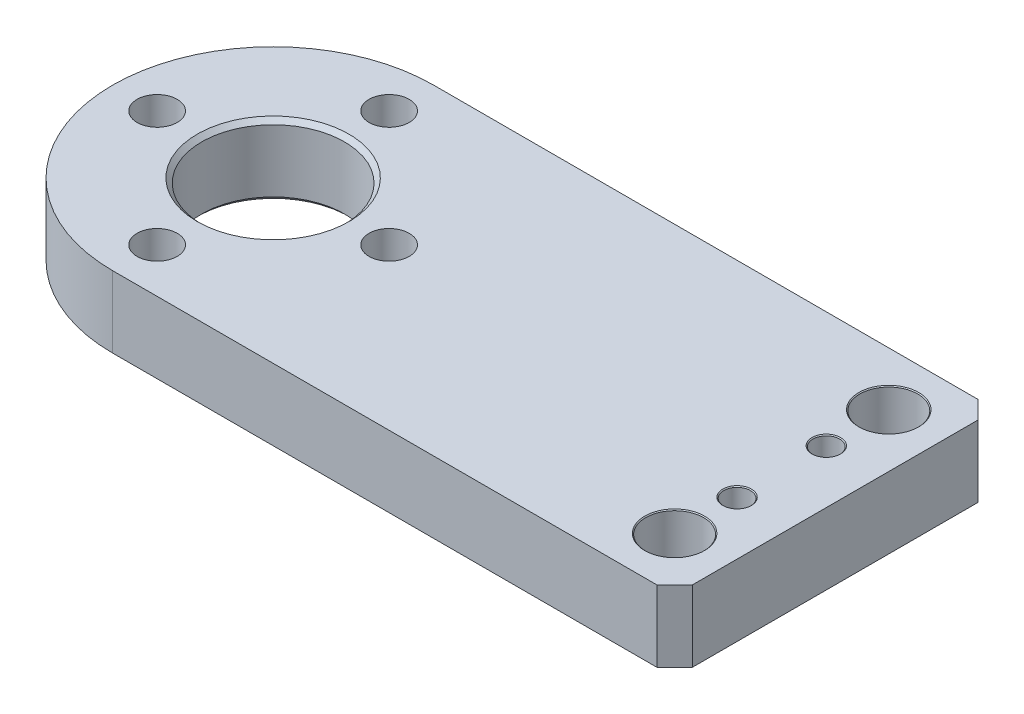
SolidWorks part; units mm, degrees
ref_plane "Front Plane" through (0, 0, 0) normal (0, 0, 1) x (1, 0, 0)
ref_plane "Top Plane" through (0, 0, 0) normal (0, 1, 0) x (1, 0, 0)
ref_plane "Right Plane" through (0, 0, 0) normal (1, 0, 0) x (0, 0, -1)
sketch "Sketch1" plane through (0, 0, 0) normal (0, 1, 0) x (1, 0, 0)
  line L0 (0, 0) -> (67.6829, 0) construction
  line L1 (0, 18) -> (61, 18)
  line L2 (63, 16) -> (63, -16)
  line L3 (0, -18) -> (61, -18)
  line L4 (61, 18) -> (63, 16)
  line L5 (61, -18) -> (63, -16)
  line L6 (0, 0) -> (0, 13) construction
  arc A0 (0, 18) -> (0, -18) centre (0, 0) ccw
  circle A1 centre (0, 0) radius 13 construction
  circle A2 centre (0, 0) radius 8
  circle A3 centre (0, 13) radius 2.25
  circle A4 centre (13, 0) radius 2.25
  circle A5 centre (0, -13) radius 2.25
  circle A6 centre (-13, 0) radius 2.25
  point P4 (63, 18)
  point P7 (63, -18)
  point P8 (63, 0)
  dimension "D1" = 18
  dimension "D4" = 26
  dimension "D5" = 16
  dimension "D8" = 4.5
  dimension "D2" = 63
  dimension "D3" = 36
  dimension "D9" = 4
extrude "Boss-Extrude1" add sketch "Sketch1" along normal blind 8
sketch "Sketch2" plane through (0, 8, 0) normal (0, 1, 0) x (1, 0, 0)
  line L0 (0, 0) -> (70.3678, 0) construction
  circle A0 centre (57, 12) radius 3.25
  circle A1 centre (57, 5) radius 1.5
  circle A2 centre (57, -5) radius 1.5
  circle A3 centre (57, -12) radius 3.25
  dimension "D1" = 3
  dimension "D2" = 6.5
  dimension "D3" = 10
  dimension "D4" = 24
  dimension "D5" = 57
extrude "Cut-Extrude1" cut sketch "Sketch2" against normal through all
chamfer "Chamfer1" distance 0.5 angle 45 2 edges at (0, 0, 8) (0, 8, 8)
chamfer "Chamfer2" distance 0.1 angle 45 8 edges at (57, 0, -8.75) (57, 0, -3.5) (57, 0, 3.5) (57, 0, 8.75) (57, 8, -8.75) (57, 8, -3.5) (57, 8, 3.5) (57, 8, 8.75)
